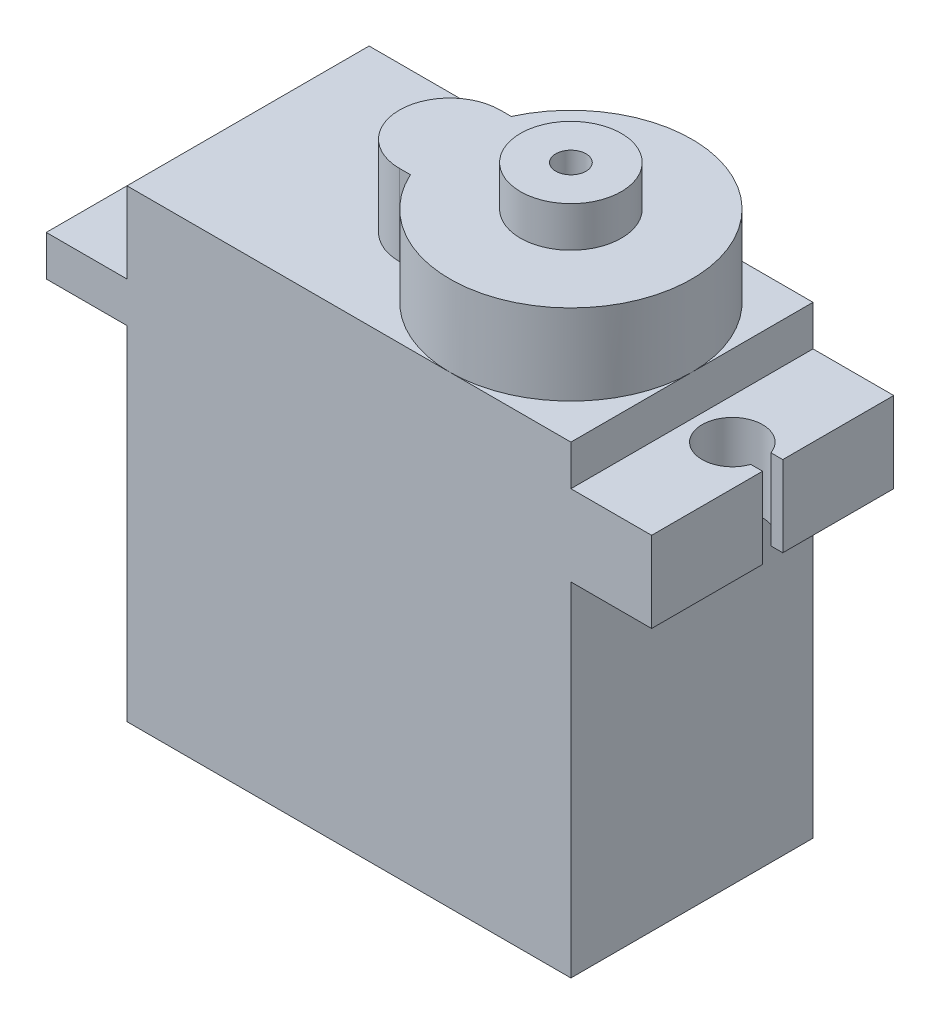
SolidWorks part; units mm, degrees
ref_plane "Alzado" through (0, 0, 0) normal (0, 0, 1) x (1, 0, 0)
ref_plane "Planta" through (0, 0, 0) normal (0, 1, 0) x (1, 0, 0)
ref_plane "Vista lateral" through (0, 0, 0) normal (1, 0, 0) x (0, 0, -1)
sketch "Croquis1" plane through (0, 0, 0) normal (0, 0, 1) x (1, 0, 0)
  line L0 (-36.1403, 11.0751) -> (-14.1403, 11.0751)
  line L1 (-14.1403, 11.0751) -> (-14.1403, -11.9249)
  line L2 (-14.1403, -11.9249) -> (-36.1403, -11.9249)
  line L3 (-36.1403, -11.9249) -> (-36.1403, 11.0751)
extrude "Saliente-Extruir1" add sketch "Croquis1" along normal blind 12
sketch "Croquis2" plane through (-14.1403, 0, 0) normal (1, 0, 0) x (0, 0, -1)
  line L0 (-12, 11.0751) -> (-12, 7.0751) construction
  line L1 (-12, -11.9249) -> (-12, 11.0751) construction
  line L2 (-12, 7.0751) -> (0, 7.0751)
  line L3 (0, -11.9249) -> (0, 11.0751) construction
  line L4 (0, 7.0751) -> (0, 5.0751)
  line L5 (0, 5.0751) -> (-12, 5.0751)
  line L6 (-12, 5.0751) -> (-12, 7.0751)
extrude "Saliente-Extruir2" add sketch "Croquis2" along normal blind 5
sketch "Croquis3" plane through (0, 7.0751, 0) normal (0, 1, 0) x (1, 0, 0)
  line L0 (-9.1403, -12) -> (-9.1403, 0) construction
  line L1 (-9.1403, 0) -> (-9.1403, -6) construction
  line L2 (-10.1403, -6) -> (-12.1403, -6) construction
  line L3 (-12.1403, -6) -> (-12.1403, -4.5) construction
  line L4 (-12.1403, -4.5) -> (-10.6403, -4.5) construction
  line L5 (-10.6403, -4.5) -> (-10.6403, -7.5) construction
  line L6 (-10.6403, -7.5) -> (-13.6403, -7.5) construction
  line L7 (-13.6403, -7.5) -> (-13.6403, -4.5) construction
  line L8 (-13.6403, -4.5) -> (-12.1403, -4.5) construction
  line L9 (-10.1403, -6) -> (-10.1403, -5.5) construction
  line L10 (-10.1403, -6) -> (-10.1403, -6.5) construction
  line L11 (-10.1403, -5.5) -> (-10.7261, -5.5)
  line L12 (-10.7261, -6.5) -> (-10.1403, -6.5)
  line L14 (-9.1403, -2.0976) -> (-10.1403, -2.0976) construction
  line L15 (-10.1403, -5.5) -> (-10.1403, 0)
  line L16 (-9.1403, 0) -> (-14.1403, 0) construction
  line L17 (-10.1403, 0) -> (-9.1403, 0)
  line L18 (-9.1403, 0) -> (-9.1403, -12)
  line L19 (-9.1403, -12) -> (-10.1403, -12)
  line L20 (-9.1403, -12) -> (-14.1403, -12) construction
  line L21 (-10.1403, -12) -> (-10.1403, -6.5)
  arc A0 (-10.7261, -6.5) -> (-10.7261, -5.5) centre (-12.1403, -6) cw
extrude "Cortar-Extruir2" cut sketch "Croquis3" against normal blind 2
mirror "Simetría1" about plane through (-9.1403, 7.0751, 12) normal (0, -1, 0) of "Saliente-Extruir2", "Cortar-Extruir2"
sketch "Croquis13" plane through (-36.1403, 0, 0) normal (-1, 0, 0) x (0, 0, 1)
  line L0 (0, 11.0751) -> (0, 7.0751) construction
  line L1 (0, 11.0751) -> (0, -11.9249) construction
  line L2 (0, 7.0751) -> (12, 7.0751)
  line L3 (12, 11.0751) -> (12, -11.9249) construction
  line L4 (12, 7.0751) -> (12, 5.0751)
  line L5 (12, 5.0751) -> (0, 5.0751)
  line L6 (0, 5.0751) -> (0, 7.0751)
extrude "Saliente-Extruir3" add sketch "Croquis13" along normal blind 4
sketch "Croquis14" plane through (0, 7.0751, 0) normal (0, 1, 0) x (1, 0, 0)
  line L0 (-40.1403, -6) -> (-40.1403, -5.5) construction
  line L1 (-40.1403, 0) -> (-40.1403, -12) construction
  line L2 (-40.1403, -12) -> (-40.1403, -6) construction
  line L3 (-40.1403, -6.5) -> (-40.1403, -5.5)
  line L4 (-36.6403, -6) -> (-36.6403, -4.5) construction
  line L5 (-36.6403, -4.5) -> (-39.6403, -4.5) construction
  line L6 (-39.6403, -4.5) -> (-39.6403, -7.5) construction
  line L7 (-39.6403, -7.5) -> (-36.6403, -7.5) construction
  line L8 (-36.6403, -7.5) -> (-36.6403, -6) construction
  line L9 (-40.1403, -6) -> (-40.1403, -6.5) construction
  line L10 (-40.1403, -6.5) -> (-39.5545, -6.5)
  line L11 (-40.1403, -5.5) -> (-39.5545, -5.5)
  line L12 (-39.6403, -6) -> (-36.6403, -6) construction
  arc A0 (-39.5545, -5.5) -> (-39.5545, -6.5) centre (-38.1403, -6) cw
extrude "Cortar-Extruir3" cut sketch "Croquis14" against normal blind 2
sketch "Croquis15" plane through (0, 11.0751, 0) normal (0, 1, 0) x (1, 0, 0)
  line L0 (-14.1403, 0) -> (-14.1403, -12) construction
  line L1 (-14.1403, -12) -> (-14.1403, -6) construction
  line L2 (-14.1403, -6) -> (-20.1403, -6) construction
  line L3 (-20.1403, -6) -> (-20.1403, 0) construction
  line L4 (-14.1403, 0) -> (-36.1403, 0) construction
  line L5 (-20.1403, 0) -> (-20.1403, -12) construction
  line L6 (-14.1403, -12) -> (-36.1403, -12) construction
  line L7 (-20.1403, -6) -> (-26.1403, -6) construction
  line L8 (-26.1403, -6) -> (-26.1403, 0) construction
  line L9 (-26.1403, 0) -> (-26.1403, -12) construction
  line L10 (-26.1403, -6) -> (-26.1403, -3.5) construction
  line L11 (-26.1403, -3.5) -> (-28.6403, -3.5) construction
  line L12 (-28.6403, -3.5) -> (-28.6403, -8.5) construction
  line L13 (-28.6403, -8.5) -> (-26.1403, -8.5) construction
  line L14 (-26.1403, -8.5) -> (-25.5947, -8.5)
  line L15 (-26.1403, -3.5) -> (-25.5947, -3.5)
  arc A0 (-26.1403, -8.5) -> (-26.1403, -3.5) centre (-26.1403, -6) cw
  arc A1 (-25.5947, -3.5) -> (-25.5947, -8.5) centre (-20.1403, -6) cw
extrude "Saliente-Extruir4" add sketch "Croquis15" along normal blind 4 contours A1 L15 A0 L14
sketch "Croquis16" plane through (0, 11.0751, 0) normal (0, 1, 0) x (1, 0, 0)
  line L0 (-14.1403, -6) -> (-20.1403, -6) construction
  line L1 (-14.1403, -12) -> (-14.1403, 0) construction
  circle A0 centre (-20.1403, -6) radius 2.5
extrude "Saliente-Extruir5" add sketch "Croquis16" along normal blind 6
sketch "Croquis21" plane through (0, 17.0751, 0) normal (0, 1, 0) x (1, 0, 0)
  circle A0 centre (-20.1403, -6) radius 0.75
extrude "Cortar-Extruir6" cut sketch "Croquis21" against normal blind 2
